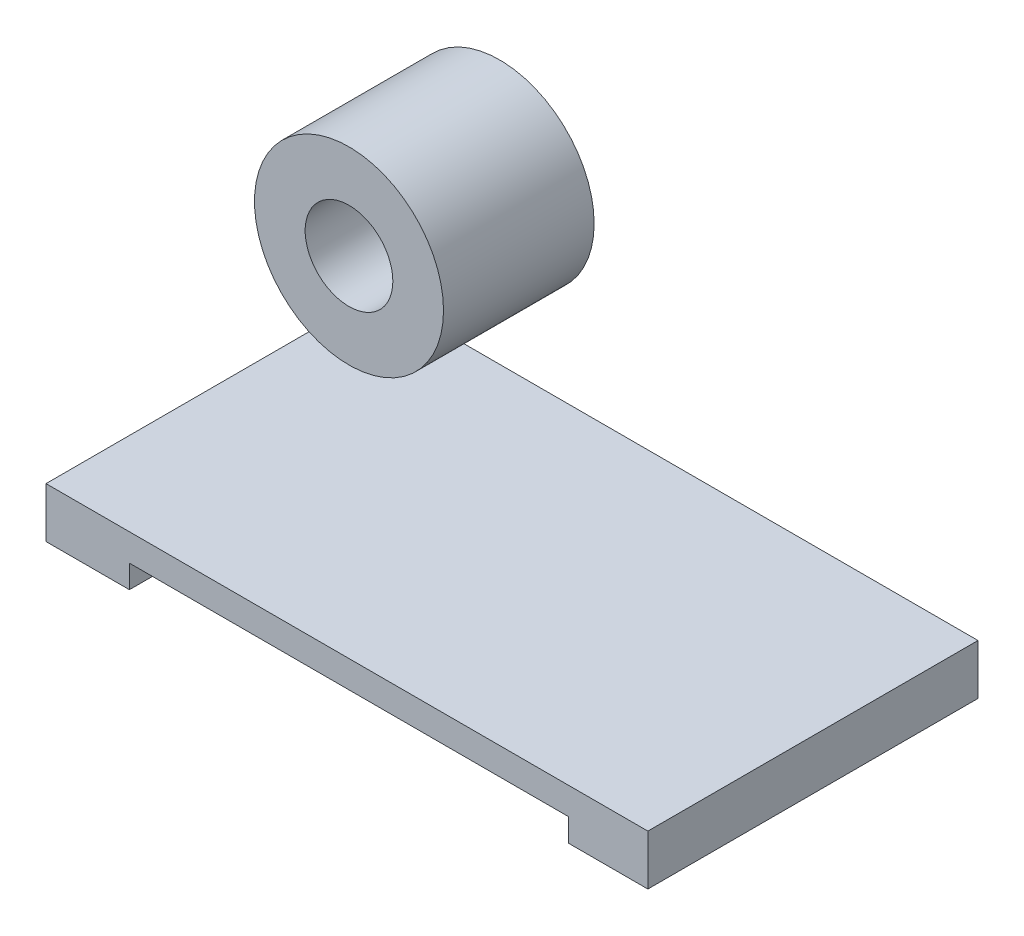
SolidWorks part; units mm, degrees
ref_plane "前视基准面" through (0, 0, 0) normal (0, 0, 1) x (1, 0, 0)
ref_plane "上视基准面" through (0, 0, 0) normal (0, 1, 0) x (1, 0, 0)
ref_plane "右视基准面" through (0, 0, 0) normal (1, 0, 0) x (0, 0, -1)
sketch "草图1" plane through (0, 0, 0) normal (0, 1, 0) x (1, 0, 0)
  line L1 (0, 0) -> (119.8843, 0)
  line L2 (0, 0) -> (0, 65.7569)
  line L3 (0, 65.7569) -> (119.8843, 65.7569)
  line L4 (119.8843, 0) -> (119.8843, 65.7569)
extrude "凸台-拉伸1" add sketch "草图1" along normal blind 10
sketch "草图2" plane through (0, 0, 0) normal (0, 0, 1) x (1, 0, 0)
  line L1 (16.6137, 4.5893) -> (104.092, 4.5893)
  line L2 (16.6137, 4.5893) -> (16.6137, -7.5947)
  line L3 (16.6137, -7.5947) -> (104.092, -7.5947)
  line L4 (104.092, 4.5893) -> (104.092, -7.5947)
extrude "切除-拉伸1" cut sketch "草图2" against normal blind 105
sketch "草图3" plane through (0, 0, 0) normal (0, 0, 1) x (1, 0, 0)
  circle A0 centre (60.3529, 79.4529) radius 18.8279
  circle A1 centre (60.3529, 79.4529) radius 8.7324
extrude "凸台-拉伸2" add sketch "草图3" against normal blind 30 separate body
